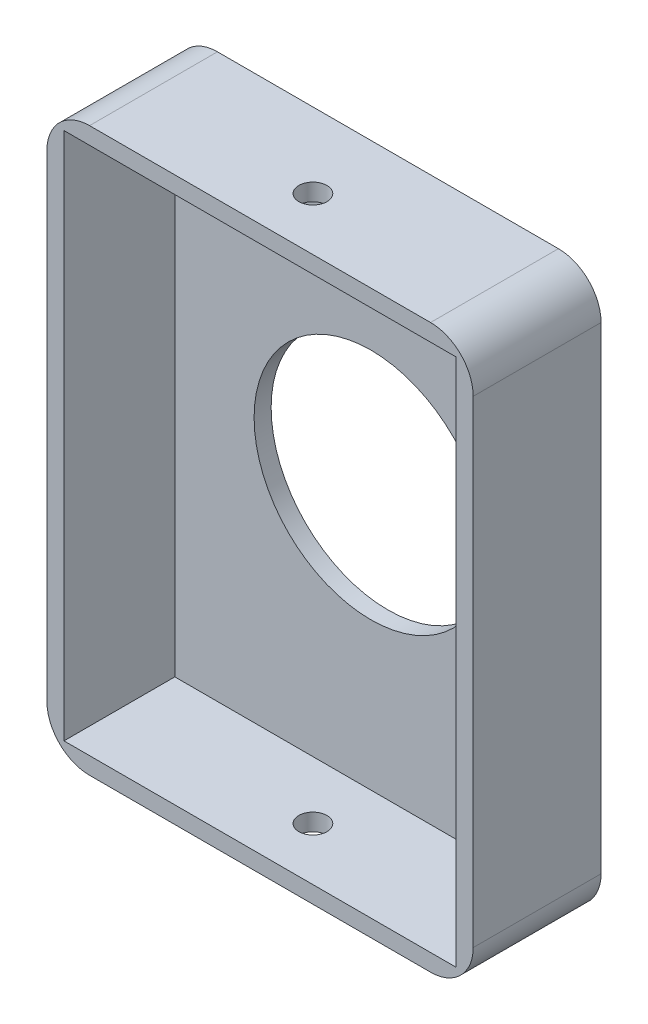
SolidWorks part; units mm, degrees
ref_plane "Front Plane" through (0, 0, 0) normal (0, 0, 1) x (1, 0, 0)
ref_plane "Top Plane" through (0, 0, 0) normal (0, 1, 0) x (1, 0, 0)
ref_plane "Right Plane" through (0, 0, 0) normal (1, 0, 0) x (0, 0, -1)
sketch "Sketch1" plane through (0, 0, 0) normal (0, 0, 1) x (1, 0, 0)
  line L1 (-31.75, -41.91) -> (31.75, -41.91)
  line L2 (-31.75, -41.91) -> (-31.75, 41.91)
  line L3 (-31.75, 41.91) -> (31.75, 41.91)
  line L4 (31.75, -41.91) -> (31.75, 41.91)
  line L5 (-31.75, -41.91) -> (31.75, 41.91) construction
  line L6 (-31.75, 41.91) -> (31.75, -41.91) construction
  point P0 (0, 0)
  dimension "D1" = 63.5
  dimension "D2" = 83.82
extrude "Boss-Extrude1" add sketch "Sketch1" along normal blind 19.05
shell "Shell1" thickness 2.54
fillet "Fillet3" [suppressed] radius 10
sketch "Sketch2" plane through (0, 0, 2.54) normal (0, 0, 1) x (1, 0, 0)
  circle A0 centre (0, 0) radius 17.399
  dimension "D1" = 34.798
extrude "Cut-Extrude1" cut sketch "Sketch2" against normal up to next
fillet "Fillet4" radius 6.35 4 edges at (31.75, 41.91, 9.525) (31.75, -41.91, 9.525) (-31.75, -41.91, 9.525) (-31.75, 41.91, 9.525)
sketch "Sketch3" plane through (0, 41.91, 0) normal (0, 1, 0) x (1, 0, 0)
  circle A0 centre (0, -11.176) radius 2.0955
  dimension "D1" = 4.191
  dimension "D2" = 11.176
extrude "Cut-Extrude2" cut sketch "Sketch3" against normal through all both and the other way through all
